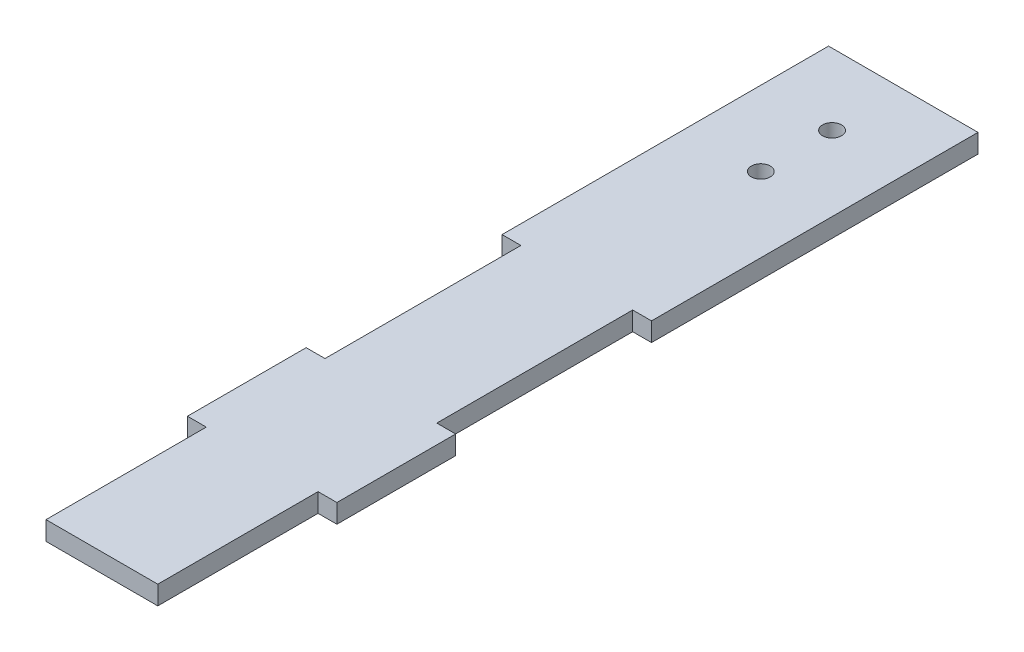
SolidWorks part; units mm, degrees
ref_plane "Front Plane" through (0, 0, 0) normal (0, 0, 1) x (1, 0, 0)
ref_plane "Top Plane" through (0, 0, 0) normal (0, 1, 0) x (1, 0, 0)
ref_plane "Right Plane" through (0, 0, 0) normal (1, 0, 0) x (0, 0, -1)
sketch "Sketch1" plane through (0, 0, 0) normal (0, 1, 0) x (1, 0, 0)
  line L0 (-12.5875, 0) -> (12.5875, 0)
  line L1 (12.5875, 0) -> (12.5875, -55)
  line L2 (12.5875, -55) -> (9.415, -55)
  line L3 (9.415, -55) -> (9.415, -88)
  line L4 (9.415, -88) -> (12.59, -88)
  line L5 (12.59, -88) -> (12.59, -108)
  line L6 (12.59, -108) -> (9.415, -108)
  line L7 (9.415, -108) -> (9.415, -135)
  line L8 (9.415, -135) -> (-9.415, -135)
  line L9 (0, 0) -> (0, -135) construction
  line L10 (-9.415, -108) -> (-9.415, -135)
  line L11 (-12.59, -108) -> (-9.415, -108)
  line L12 (-12.59, -88) -> (-12.59, -108)
  line L13 (-9.415, -88) -> (-12.59, -88)
  line L14 (-9.415, -55) -> (-9.415, -88)
  line L15 (-12.5875, -55) -> (-9.415, -55)
  line L16 (-12.5875, 0) -> (-12.5875, -55)
  dimension "D1" = 55
  dimension "D2" = 3.175
  dimension "D3" = 20
  dimension "D4" = 33
  dimension "D5" = 27
  dimension "D6" = 12.5875
  dimension "D7" = 9.415
  dimension "D8" = 0
extrude "Boss-Extrude1" add sketch "Sketch1" along normal blind 3.175
sketch "Sketch2" plane through (0, 3.175, 0) normal (0, 1, 0) x (1, 0, 0)
  circle A0 centre (0, -24) radius 1.6 construction
  circle A1 centre (0, -12) radius 1.6 construction
  circle A2 centre (0, -24) radius 1.6
  circle A3 centre (0, -12) radius 1.6
extrude "Cut-Extrude1" cut sketch "Sketch2" against normal through all both and the other way through all
